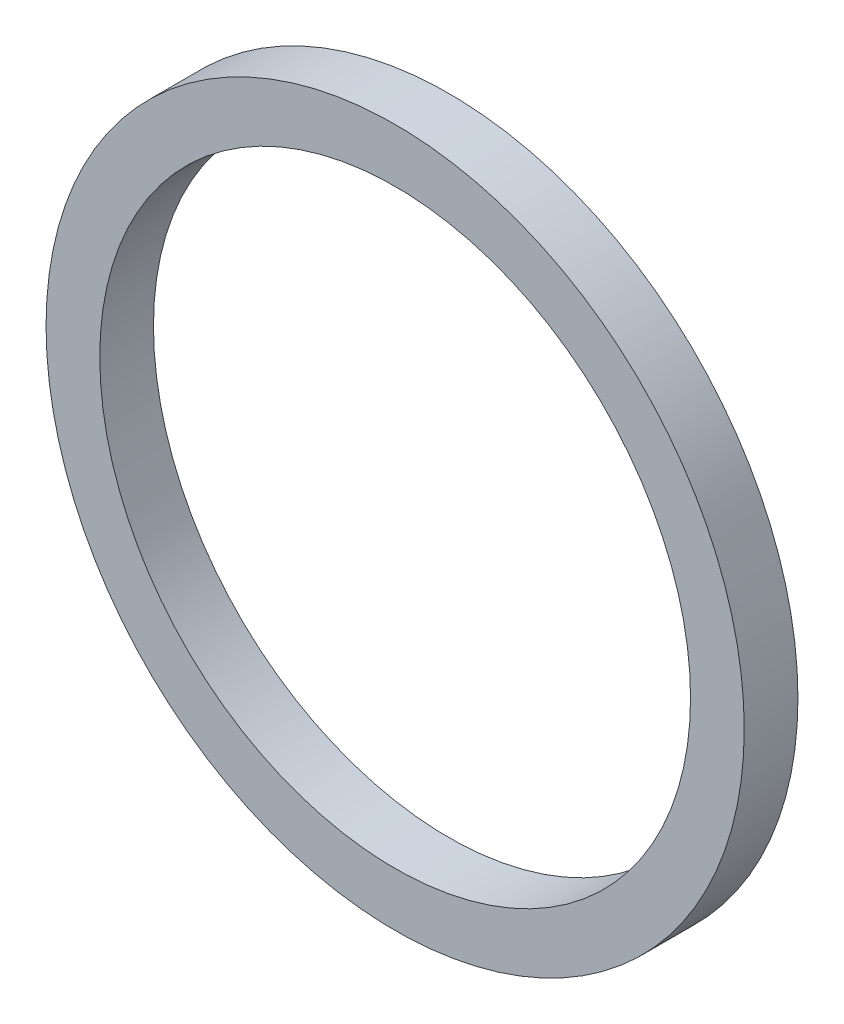
SolidWorks part; units mm, degrees
ref_plane "Front Plane" through (0, 0, 0) normal (0, 0, 1) x (1, 0, 0)
ref_plane "Top Plane" through (0, 0, 0) normal (0, 1, 0) x (1, 0, 0)
ref_plane "Right Plane" through (0, 0, 0) normal (1, 0, 0) x (0, 0, -1)
sketch "Sketch2" plane through (0, 0, 0) normal (0, 0, 1) x (1, 0, 0)
  circle A0 centre (0, 0) radius 32.5
  dimension "D1" = 65
extrude "Boss-Extrude1" add sketch "Sketch2" along normal mid plane 5
sketch "Sketch3" plane through (0, 0, 2.5) normal (0, 0, 1) x (1, 0, 0)
  circle A0 centre (0, 0) radius 27.5
  dimension "D1" = 55
extrude "Cut-Extrude1" cut sketch "Sketch3" against normal blind 5 contours A0
